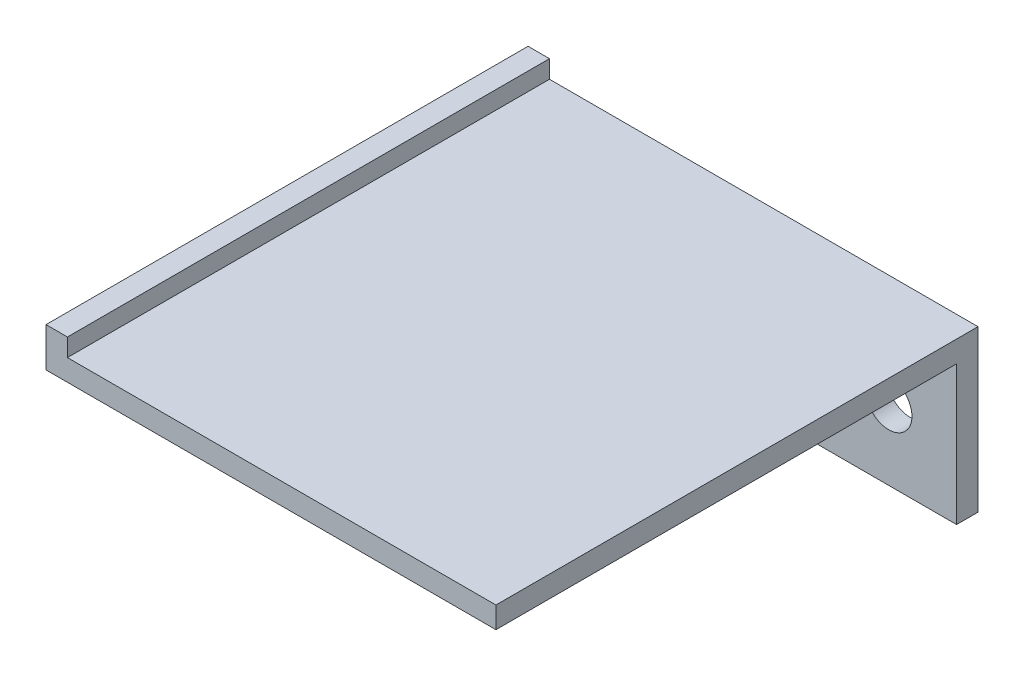
SolidWorks part; units mm, degrees
ref_plane "前视基准面" through (0, 0, 0) normal (0, 0, 1) x (1, 0, 0)
ref_plane "上视基准面" through (0, 0, 0) normal (0, 1, 0) x (1, 0, 0)
ref_plane "右视基准面" through (0, 0, 0) normal (1, 0, 0) x (0, 0, -1)
sketch "草图1" plane through (0, 0, 0) normal (0, 1, 0) x (1, 0, 0)
  line L1 (0, 0) -> (240, 0)
  line L2 (0, 0) -> (0, 270)
  line L3 (0, 270) -> (240, 270)
  line L4 (240, 0) -> (240, 270)
  dimension "D1" = 240
  dimension "D2" = 270
extrude "凸台-拉伸1" add sketch "草图1" along normal blind 12
sketch "草图2" plane through (0, 0, 0) normal (-1, 0, 0) x (0, 0, 1)
  line L0 (-270, 12) -> (0, 12) construction
  line L1 (-270, 22) -> (0, 22)
  line L2 (-270, 22) -> (-270, -78)
  line L3 (-270, -78) -> (0, -78)
  line L4 (0, 22) -> (0, -78)
  line L5 (0, 12) -> (0, 0) construction
  line L7 (-270, 12) -> (-270, 0) construction
  dimension "D1" = 10
  dimension "D2" = 100
extrude "凸台-拉伸2" add sketch "草图2" along normal blind 12
sketch "草图3" plane through (0, 0, 0) normal (1, 0, 0) x (0, 0, -1)
  line L0 (270, 0) -> (0, 0) construction
  line L1 (270, -78) -> (258, -78)
  line L2 (270, -78) -> (270, 0)
  line L3 (270, 0) -> (258, 0)
  line L4 (258, -78) -> (258, 0)
  dimension "D1" = 12
extrude "凸台-拉伸3" add sketch "草图3" along normal blind 240
sketch "草图4" plane through (0, 0, -258) normal (0, 0, 1) x (1, 0, 0)
  line L0 (-813.0292, -38) -> (49186.9708, -38) construction
  line L1 (240, -78) -> (0, -78) construction
  line L2 (240, 0) -> (240, -78) construction
  circle A0 centre (82, -38) radius 13
  circle A1 centre (202, -38) radius 13
  dimension "D2" = 26
  dimension "D1" = 40
  dimension "D3" = 38
  dimension "D4" = 120
extrude "切除-拉伸1" cut sketch "草图4" against normal through all
sketch "草图5" plane through (-12, 0, 0) normal (-1, 0, 0) x (0, 0, 1)
  line L0 (-1227.097, -38) -> (48772.903, -38) construction
  line L1 (-270, -78) -> (0, -78) construction
  line L2 (-270, 22) -> (-270, -78) construction
  line L3 (-100, -78) -> (0, 0)
  line L4 (0, -78) -> (0, 22) construction
  line L5 (0, 0) -> (0, -78)
  line L6 (0, -78) -> (-100, -78)
  circle A0 centre (-217, -38) radius 13
  circle A1 centre (-137, -38) radius 13
  dimension "D1" = 26
  dimension "D2" = 40
  dimension "D3" = 53
  dimension "D4" = 80
  dimension "D5" = 37
extrude "切除-拉伸2" cut sketch "草图5" against normal through all
